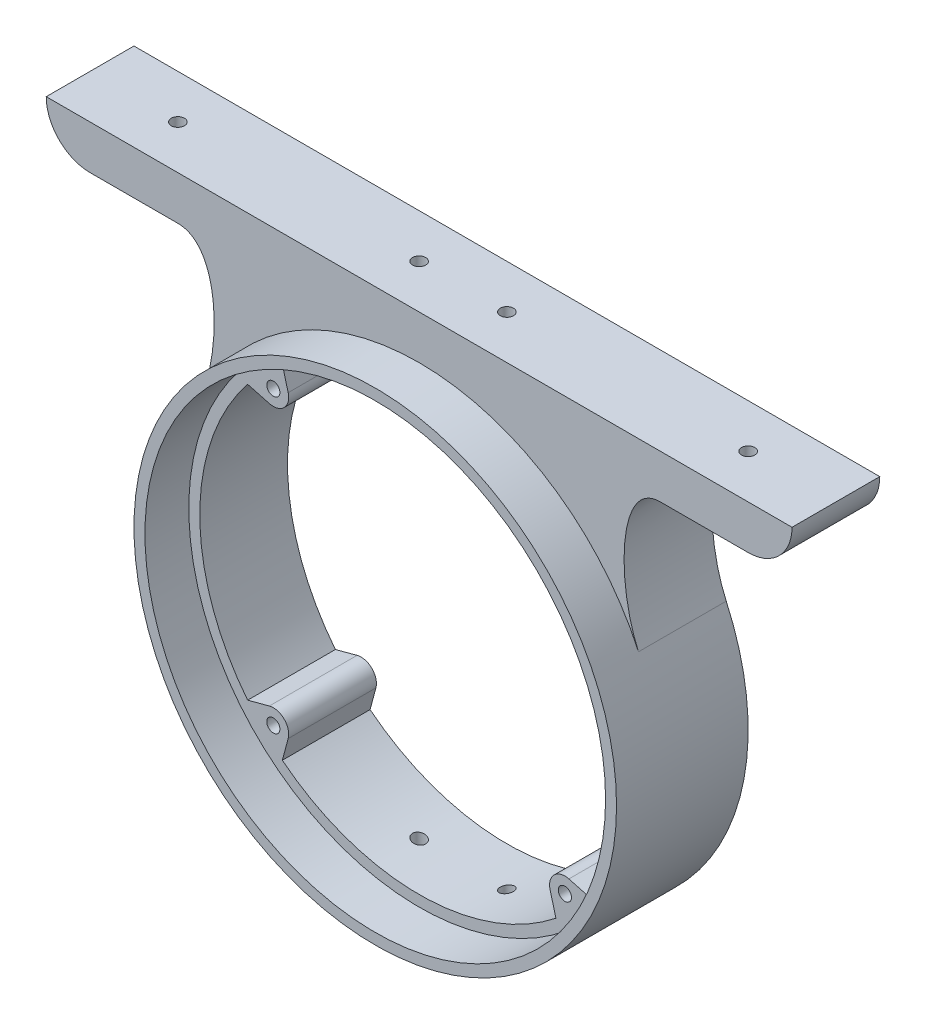
SolidWorks part; units mm, degrees
material "ABS"
ref_plane "前视基准面" through (0, 0, 0) normal (0, 0, 1) x (1, 0, 0)
ref_plane "上视基准面" through (0, 0, 0) normal (0, 1, 0) x (1, 0, 0)
ref_plane "右视基准面" through (0, 0, 0) normal (1, 0, 0) x (0, 0, -1)
sketch "草图2" plane through (0, 0, 0) normal (0, 0, 1) x (1, 0, 0)
  line L0 (0, 55) -> (37.8067, 55) construction
  line L1 (-55, 0) -> (-55, 32.093) construction
  line L2 (-45, 109.1596) -> (-45, 87.8343) construction
  line L3 (-55, 55) -> (-85, 55) construction
  line L4 (-85, 55) -> (-85, 65) construction
  line L5 (-75, 55) -> (-55, 55)
  line L6 (0, 104.3034) -> (0, 77.4884) construction
  line L7 (85, 55) -> (85, 65) construction
  line L8 (55, 55) -> (85, 55) construction
  line L9 (75, 55) -> (55, 55)
  line L10 (-85, 65) -> (85, 65)
  line L13 (-50, 22.9129) -> (-45, 33.8238) construction
  line L14 (-45, 33.8238) -> (-45, 55) construction
  line L15 (-45, 55) -> (-55, 55) construction
  line L16 (50, 22.9129) -> (45, 33.8238) construction
  line L17 (45, 33.8238) -> (45, 55) construction
  line L18 (45, 55) -> (55, 55) construction
  circle A1 centre (0, 0) radius 55 construction
  arc A2 (-85, 65) -> (-75, 55) centre (-75, 65) ccw
  arc A3 (85, 65) -> (75, 55) centre (75, 65) cw
  arc A4 (-50, 22.9129) -> (50, 22.9129) centre (0, 0) ccw
  circle A7 centre (0, 0) radius 50
  spline S0 degree 3 poles (-50, 22.9129) (-45, 33.8238) (-45, 55) (-55, 55) knots 0 0 0 0 1 1 1 1
  spline S1 degree 3 poles (50, 22.9129) (45, 33.8238) (45, 55) (55, 55) knots 0 0 0 0 1 1 1 1
  dimension "D1" = 110
  dimension "D2" = 100
  dimension "D3" = 10
  dimension "D5" = 10
  dimension "D4" = 30
  dimension "D8" = 5
extrude "凸台-拉伸1" add sketch "草图2" along normal blind 20
sketch "草图3" plane through (0, 65, 0) normal (0, 1, 0) x (1, 0, 0)
  line L0 (0, 0) -> (0, -20) construction
  line L2 (-85, -10) -> (-55.1419, -10) construction
  line L4 (-85, -20) -> (-85, 0) construction
  circle A0 centre (-65, -10) radius 1.5
  circle A1 centre (-10, -10) radius 1.5
  circle A2 centre (10, -10) radius 1.5
  circle A3 centre (65, -10) radius 1.5
  point P5 (-85, -10)
  dimension "D1" = 3
  dimension "D2" = 10
  dimension "D3" = 55
extrude "切除-拉伸1" cut sketch "草图3" against normal through all
sketch "草图4" plane through (0, 0, 0) normal (0, 0, 1) x (1, 0, 0)
  line L0 (0, 0) -> (-21.2173, 21.2173) construction
  line L1 (-31.1791, 39.0879) -> (-29.8533, 34.1399)
  line L2 (-39.0879, 31.1791) -> (-34.1399, 29.8533)
  line L3 (0, 0) -> (0, 13.1846) construction
  line L6 (31.1791, 39.0879) -> (29.8533, 34.1399)
  line L7 (39.0879, 31.1791) -> (34.1399, 29.8533)
  line L8 (39.0879, -31.1791) -> (34.1399, -29.8533)
  line L9 (31.1791, -39.0879) -> (29.8533, -34.1399)
  line L10 (-31.1791, -39.0879) -> (-29.8533, -34.1399)
  line L11 (-39.0879, -31.1791) -> (-34.1399, -29.8533)
  line L12 (0, 0) -> (-74.7871, 0) construction
  circle A0 centre (-33.234, 33.234) radius 1.5
  arc A2 (-29.8533, 34.1399) -> (-34.1399, 29.8533) centre (-33.234, 33.234) cw
  arc A3 (-31.1791, 39.0879) -> (-39.0879, 31.1791) centre (0, 0) ccw
  circle A7 centre (0, 0) radius 50 construction
  arc A8 (34.1399, 29.8533) -> (29.8533, 34.1399) centre (33.234, 33.234) cw
  arc A9 (39.0879, 31.1791) -> (31.1791, 39.0879) centre (0, 0) ccw
  circle A10 centre (33.234, 33.234) radius 1.5
  arc A11 (29.8533, -34.1399) -> (34.1399, -29.8533) centre (33.234, -33.234) cw
  arc A12 (31.1791, -39.0879) -> (39.0879, -31.1791) centre (0, 0) ccw
  circle A13 centre (33.234, -33.234) radius 1.5
  arc A14 (-34.1399, -29.8533) -> (-29.8533, -34.1399) centre (-33.234, -33.234) cw
  arc A15 (-39.0879, -31.1791) -> (-31.1791, -39.0879) centre (0, 0) ccw
  circle A16 centre (-33.234, -33.234) radius 1.5
  point P35 (0, 0)
  dimension "D1" = 30
  dimension "D2" = 2
  dimension "D3" = 3
  dimension "D5" = 4
  dimension "D4" = 47
  dimension "D6" = 45
extrude "凸台-拉伸2" add sketch "草图4" along normal through all
sketch "草图6" plane through (0, 0, 0) normal (0, 1, 0) x (1, 0, 0)
  line L0 (85, 0) -> (-85, 0) construction
  line L1 (-8.4123, -7.25) -> (-11.5877, -7.25)
  line L2 (-11.5877, -7.25) -> (-13.1754, -10)
  line L3 (-13.1754, -10) -> (-11.5877, -12.75)
  line L4 (-11.5877, -12.75) -> (-8.4123, -12.75)
  line L5 (-8.4123, -12.75) -> (-6.8246, -10)
  line L6 (-6.8246, -10) -> (-8.4123, -7.25)
  line L7 (0, 0) -> (0, -20) construction
  line L8 (85, -20) -> (-85, -20) construction
  line L9 (6.8246, -10) -> (8.4123, -7.25)
  line L10 (8.4123, -12.75) -> (6.8246, -10)
  line L11 (11.5877, -12.75) -> (8.4123, -12.75)
  line L12 (13.1754, -10) -> (11.5877, -12.75)
  line L13 (11.5877, -7.25) -> (13.1754, -10)
  line L14 (8.4123, -7.25) -> (11.5877, -7.25)
  circle A0 centre (-10, -10) radius 2.75 construction
  circle A1 centre (10, -10) radius 2.75 construction
  point P11 (-12.3816, -11.375)
  dimension "D1" = 5.5
extrude "切除-拉伸4" cut sketch "草图6" against normal through all from offset 52 offset against normal yes
sketch "草图7" plane through (0, 55, 0) normal (0, -1, 0) x (1, 0, 0)
  line L0 (-75, 20) -> (-55, 20) construction
  line L1 (-63.4123, 12.75) -> (-66.5877, 12.75)
  line L2 (-66.5877, 12.75) -> (-68.1754, 10)
  line L3 (-68.1754, 10) -> (-66.5877, 7.25)
  line L4 (-66.5877, 7.25) -> (-63.4123, 7.25)
  line L5 (-63.4123, 7.25) -> (-61.8246, 10)
  line L6 (-61.8246, 10) -> (-63.4123, 12.75)
  line L7 (0, 0) -> (0, 40.9385) construction
  line L9 (61.8246, 10) -> (63.4123, 12.75)
  line L10 (63.4123, 7.25) -> (61.8246, 10)
  line L11 (66.5877, 7.25) -> (63.4123, 7.25)
  line L12 (68.1754, 10) -> (66.5877, 7.25)
  line L13 (66.5877, 12.75) -> (68.1754, 10)
  line L14 (63.4123, 12.75) -> (66.5877, 12.75)
  circle A0 centre (-65, 10) radius 2.75 construction
  circle A1 centre (65, 10) radius 2.75 construction
  dimension "D1" = 5.5
extrude "切除-拉伸5" cut sketch "草图7" against normal blind 2
sketch "草图9" plane through (0, 0, 20) normal (0, 0, 1) x (1, 0, 0)
  circle A0 centre (0, 0) radius 50
  circle A1 centre (0, 0) radius 55
extrude "凸台-拉伸3" add sketch "草图9" along normal blind 10
sketch "草图10" plane through (0, 0, 30) normal (0, 0, 1) x (1, 0, 0)
  circle A0 centre (0, 0) radius 50
  circle A1 centre (0, 0) radius 52.5
  circle A2 centre (0, 0) radius 50 construction
  dimension "D1" = 2.5
extrude "切除-拉伸6" cut sketch "草图10" against normal blind 10
